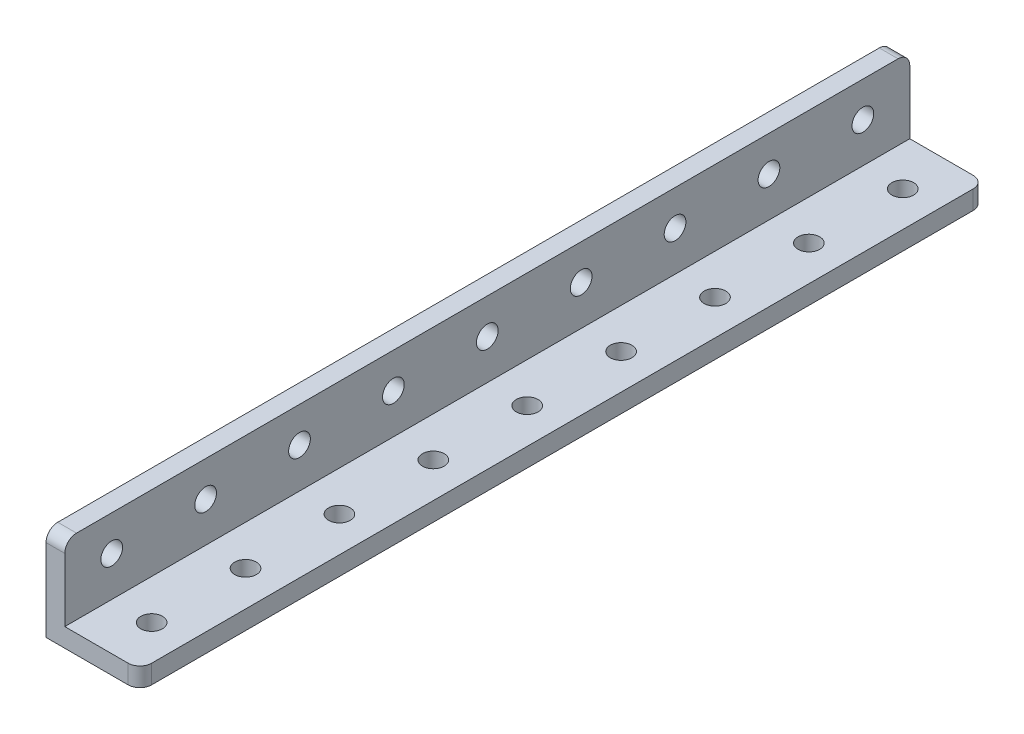
SolidWorks part; units mm, degrees
other "Defeature"
material "5052 Alloy"
ref_plane "Front Plane" through (0, 0, 0) normal (0, 0, 1) x (1, 0, 0)
ref_plane "Top Plane" through (0, 0, 0) normal (0, 1, 0) x (1, 0, 0)
ref_plane "Right Plane" through (0, 0, 0) normal (1, 0, 0) x (0, 0, -1)
sketch "Sketch1" plane through (0, 0, 0) normal (0, 0, 1) x (1, 0, 0)
  line L0 (0, 0) -> (16, 0)
  line L1 (16, 0) -> (16, 3.2)
  line L2 (16, 3.2) -> (3.2, 3.2)
  line L3 (3.2, 3.2) -> (3.2, 16)
  line L4 (3.2, 16) -> (0, 16)
  line L5 (0, 16) -> (0, 0)
  dimension "D1" = 16
  dimension "D2" = 3.2
  dimension "D3" = 16
  dimension "D4" = 3.2
extrude "Boss-Extrude1" add sketch "Sketch1" against normal mid plane 144
sketch "Sketch2" plane through (0, 0, 0) normal (-1, 0, 0) x (0, 0, 1)
  line L5 (-72, 16) -> (72, 16) construction
  line L8 (72, 3.2) -> (72, 16) construction
  circle A12 centre (64, 10) radius 1.85
  point P8 (72, 9.6)
  dimension "D1" = 3.7
  dimension "D2" = 6
  dimension "D3" = 8
extrude "Cut-Extrude1" cut sketch "Sketch2" against normal through all
sketch "Sketch3" plane through (0, 3.2, 0) normal (0, 1, 0) x (1, 0, 0)
  line L0 (16, 72) -> (16, -72) construction
  line L1 (16, -72) -> (3.2, -72) construction
  circle A0 centre (10, -64) radius 1.85
  dimension "D3" = 3.7
  dimension "D1" = 6
  dimension "D2" = 8
extrude "Cut-Extrude2" cut sketch "Sketch3" against normal up to next
pattern_linear "LPattern1" count 9 spacing 16 along (0, 0, -1) of "Cut-Extrude1", "Cut-Extrude2"
fillet "Fillet1" radius 2 4 edges at (1.6, 16, 72) (16, 1.6, 72) (16, 1.6, -72) (1.6, 16, -72)
